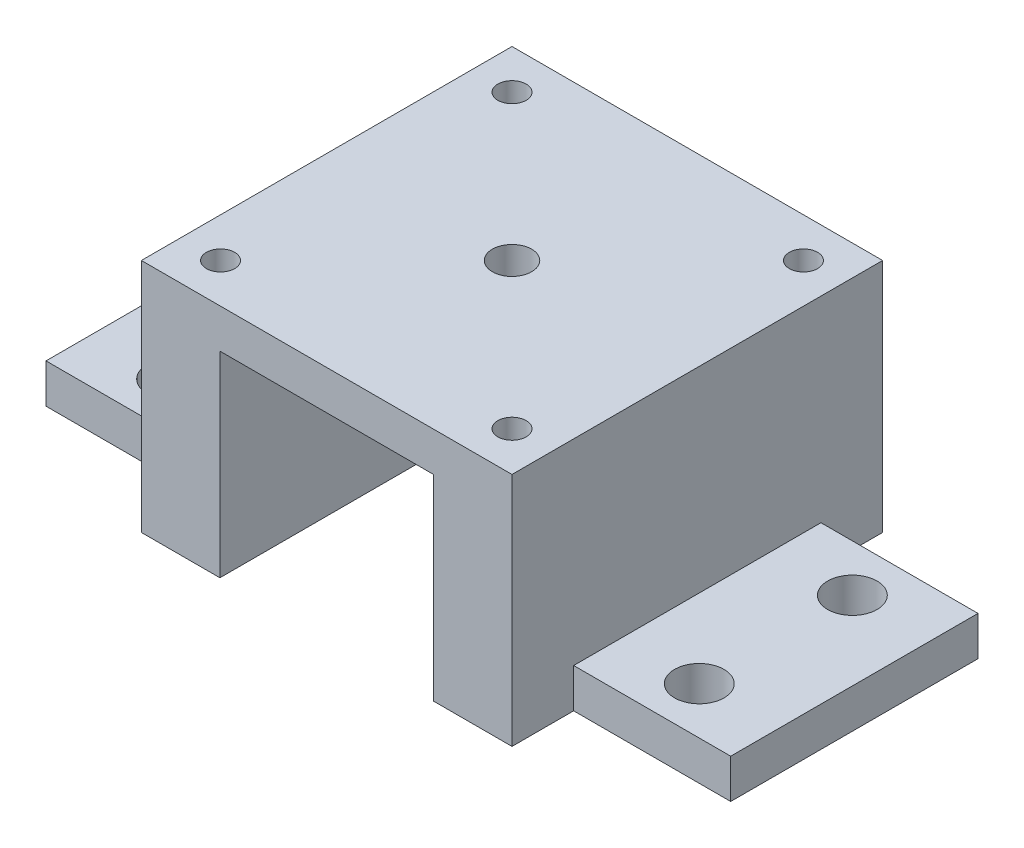
SolidWorks part; units mm, degrees
ref_plane "Front Plane" through (0, 0, 0) normal (0, 0, 1) x (1, 0, 0)
ref_plane "Top Plane" through (0, 0, 0) normal (0, 1, 0) x (1, 0, 0)
ref_plane "Right Plane" through (0, 0, 0) normal (1, 0, 0) x (0, 0, -1)
sketch "Sketch1" plane through (0, 0, 0) normal (0, 1, 0) x (1, 0, 0)
  line L1 (-59.944, 25.0118) -> (0, 25.0118)
  line L2 (-59.944, 25.0118) -> (-59.944, -34.9322)
  line L3 (-59.944, -34.9322) -> (0, -34.9322)
  line L4 (0, 25.0118) -> (0, -34.9322)
  dimension "D1" = 59.944
extrude "Boss-Extrude1" add sketch "Sketch1" along normal blind 38.1 contours L1 L4 L3 L2
sketch "Sketch2" plane through (0, 0, 34.9322) normal (0, 0, 1) x (1, 0, 0)
  line L0 (-59.944, 0) -> (0, 0) construction
  line L1 (-47.244, 0) -> (-12.7, 0)
  line L2 (-47.244, 0) -> (-47.244, 31.75)
  line L3 (-47.244, 31.75) -> (-12.7, 31.75)
  line L4 (-12.7, 0) -> (-12.7, 31.75)
  line L5 (-59.944, 38.1) -> (0, 38.1) construction
  line L6 (-59.944, 38.1) -> (-59.944, 0) construction
  line L7 (0, 38.1) -> (0, 0) construction
  dimension "D1" = 6.35
  dimension "D2" = 12.7
  dimension "D3" = 12.7
extrude "Cut-Extrude1" cut sketch "Sketch2" against normal through all
sketch "Sketch3" plane through (0, 38.1, 0) normal (0, 1, 0) x (1, 0, 0)
  line L0 (-59.944, 25.0118) -> (-59.944, -34.9322) construction
  line L2 (-59.944, -34.9322) -> (0, -34.9322) construction
  circle A0 centre (-29.972, -4.9602) radius 3.175
  point P6 (-86.8701, 28.8837)
  dimension "D3" = 6.35
  dimension "D1" = 29.972
  dimension "D2" = 29.972
extrude "Cut-Extrude2" cut sketch "Sketch3" against normal through all
sketch "Sketch4" plane through (0, 0, 0) normal (1, 0, 0) x (0, 0, -1)
  line L0 (25.0118, 0) -> (-34.9322, 0) construction
  line L1 (-24.9602, 0) -> (15.0398, 0)
  line L2 (-24.9602, 0) -> (-24.9602, 6.35)
  line L3 (-24.9602, 6.35) -> (15.0398, 6.35)
  line L4 (15.0398, 0) -> (15.0398, 6.35)
  line L5 (-34.9322, 38.1) -> (-34.9322, 0) construction
  dimension "D1" = 40
  dimension "D2" = 9.972
  dimension "D3" = 6.35
extrude "Boss-Extrude2" add sketch "Sketch4" along normal blind 25.4
sketch "Sketch5" plane through (-59.944, 0, 0) normal (-1, 0, 0) x (0, 0, 1)
  line L1 (-15.0398, 0) -> (24.9602, 0)
  line L2 (-15.0398, 0) -> (-15.0398, 6.35)
  line L3 (-15.0398, 6.35) -> (24.9602, 6.35)
  line L4 (24.9602, 0) -> (24.9602, 6.35)
  dimension "D1" = 40
  dimension "D2" = 6.35
extrude "Boss-Extrude3" add sketch "Sketch5" along normal blind 25.4
sketch "Sketch6" plane through (0, 6.35, 0) normal (0, 1, 0) x (1, 0, 0)
  line L0 (-85.344, -24.9602) -> (-85.344, 15.0398) construction
  line L1 (-85.344, 15.0398) -> (-59.944, 15.0398) construction
  line L2 (-85.344, -24.9602) -> (-59.944, -24.9602) construction
  line L3 (25.4, -24.9602) -> (0, -24.9602) construction
  line L4 (25.4, 15.0398) -> (0, 15.0398) construction
  line L5 (25.4, 15.0398) -> (25.4, -24.9602) construction
  circle A0 centre (-72.644, 7.4198) radius 4
  circle A1 centre (-72.644, -17.3402) radius 4
  circle A2 centre (12.7, 7.4198) radius 4
  circle A3 centre (12.7, -17.3402) radius 4
  point P20 (-72.2098, 42.5123)
  dimension "D5" = 8
  dimension "D1" = 12.7
  dimension "D2" = 12.7
  dimension "D3" = 7.62
  dimension "D4" = 7.62
  dimension "D6" = 7.62
  dimension "D7" = 7.62
  dimension "D8" = 12.7
  dimension "D9" = 12.7
extrude "Cut-Extrude3" cut sketch "Sketch6" against normal through all
sketch "Sketch7" plane through (0, 38.1, 0) normal (0, 1, 0) x (1, 0, 0)
  line L0 (-59.944, 25.0118) -> (-59.944, -34.9322) construction
  line L1 (-59.944, 25.0118) -> (0, 25.0118) construction
  line L2 (-53.5432, 18.611) -> (-53.5432, -34.9322) construction
  line L3 (-59.944, -34.9322) -> (0, -34.9322) construction
  line L4 (-53.5432, 18.611) -> (0, 18.611) construction
  line L5 (0, 25.0118) -> (0, -34.9322) construction
  line L6 (-6.4008, -28.5314) -> (-6.4008, 25.0118) construction
  line L7 (-6.4008, -28.5314) -> (-59.944, -28.5314) construction
  circle A0 centre (-53.5432, 18.611) radius 2.286
  circle A1 centre (-6.4008, -28.5314) radius 2.286
  circle A2 centre (-53.5432, -28.5314) radius 2.286
  circle A3 centre (-6.4008, 18.611) radius 2.286
  dimension "D1" = 4.572
  dimension "D2" = 6.4008
  dimension "D3" = 6.4008
  dimension "D4" = 6.4008
  dimension "D5" = 6.4008
extrude "Cut-Extrude4" cut sketch "Sketch7" against normal blind 12.7
equation "\"D2@Sketch4\"=(2.36in/2)-20mm"
